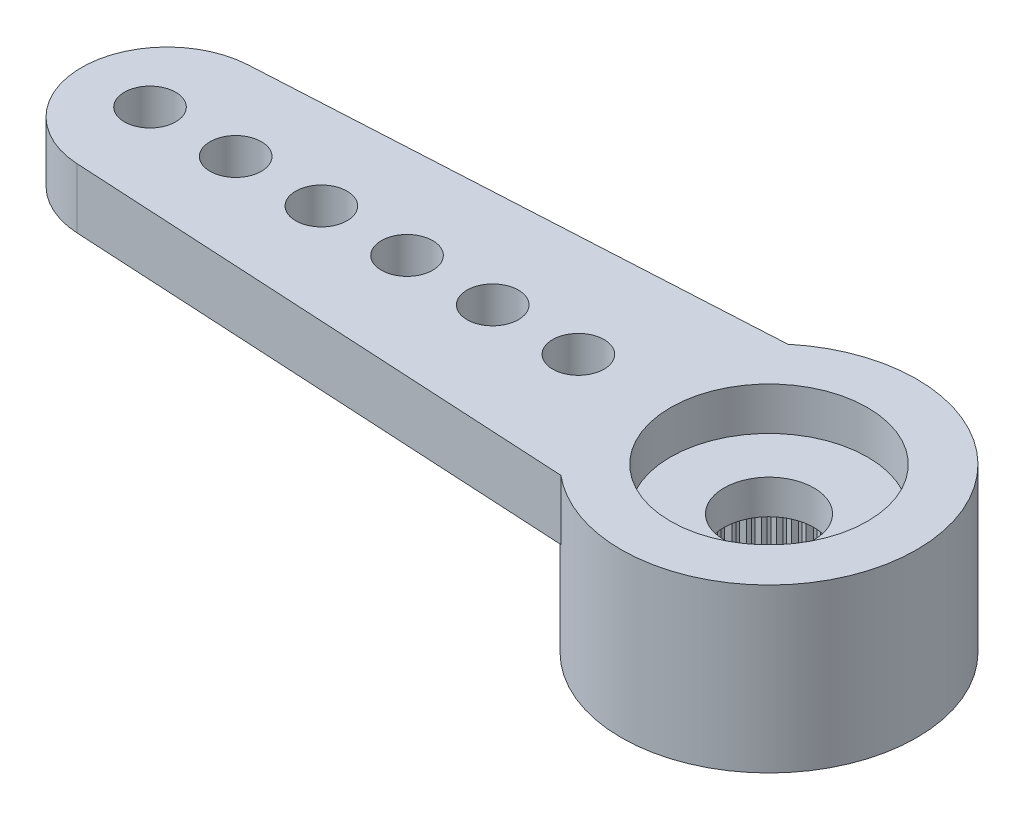
SolidWorks part; units mm, degrees
material "PVC Rígido"
ref_plane "Plano frontal" through (0, 0, 0) normal (0, 0, 1) x (1, 0, 0)
ref_plane "Plano superior" through (0, 0, 0) normal (0, 1, 0) x (1, 0, 0)
ref_plane "Plano direito" through (0, 0, 0) normal (1, 0, 0) x (0, 0, -1)
sketch "Esboço1" plane through (0, 0, 0) normal (0, 1, 0) x (1, 0, 0)
  line L0 (0, 0) -> (-14.05, 0) construction
  line L1 (-14.1591, 1.997) -> (-2.2091, 2.65)
  line L2 (-2.2091, -2.65) -> (-14.1591, -1.997)
  arc A0 (-2.2091, -2.65) -> (-2.2091, 2.65) centre (0, 0) ccw
  arc A1 (-14.1591, 1.997) -> (-14.1591, -1.997) centre (-14.05, 0) ccw
  dimension "D1" = 6.9
  dimension "D2" = 4
  dimension "D3" = 19.5
  dimension "D4" = 5.3
extrude "Ressalto-extrusão1" add sketch "Esboço1" against normal blind 1.4
sketch "Esboço2" plane through (0, -1.4, 0) normal (0, -1, 0) x (1, 0, 0)
  arc A0 (-2.2091, -2.65) -> (-2.2091, 2.65) centre (0, 0) ccw construction
  circle A1 centre (0, 0) radius 3.45
extrude "Ressalto-extrusão2" add sketch "Esboço2" along normal offset from surface (2.4 mm away) 3.8 up to face at (-7.242, 0, 0)
hole_wizard "Furo4" positions "Esboço9" profile "Esboço10" legacy end condition through all
sketch "Esboço9" plane through (0, 0, 0) normal (0, 1, 0) x (1, 0, 0)
  line L1 (-14.45, 0) -> (0, 0) construction
  arc A2 (-14.1591, 1.997) -> (-14.1591, -1.997) centre (-14.05, 0) ccw construction
  point P0 (-14.45, 0)
  point P19 (-16.05, 0)
  dimension "D1" = 1.6
sketch "Esboço10" plane through (-14.45, 0, 0) normal (1, 0, 0) x (0, 0, 1)
  line L0 (0, 0) -> (0, 3.8)
  line L1 (0, 3.8) -> (0.6, 3.8)
  line L2 (0.6, 3.8) -> (0.6, 0)
  line L3 (0.6, 0) -> (0, 0)
  line L4 (0, 110) -> (0, -10) construction
  dimension "Diameter" = 1.2
  dimension "Depth" = 3.8
pattern_linear "Padrão linear1" count 6 spacing 2 along (1, 0, 0) of "Furo4"
hole_wizard "Furo1" positions "Esboço3" profile "Esboço4" legacy
sketch "Esboço3" plane through (0, -3.8, 0) normal (0, -1, 0) x (-1, 0, 0)
  point P0 (0, 0)
sketch "Esboço4" plane through (0, -3.8, 0) normal (1, 0, 0) x (0, 0, -1)
  line L0 (0, 0) -> (0, 2)
  line L1 (0, 2) -> (2.475, 2)
  line L2 (2.475, 2) -> (2.475, 0)
  line L3 (2.475, 0) -> (0, 0)
  line L4 (0, 110) -> (0, -10) construction
  dimension "Diameter" = 4.95
  dimension "Depth" = 2
hole_wizard "Furo2" positions "Esboço5" profile "Esboço6" legacy
sketch "Esboço5" plane through (0, 0, 0) normal (0, 1, 0) x (1, 0, 0)
  point P0 (0, 0)
sketch "Esboço6" plane through (0, 0, 0) normal (1, 0, 0) x (0, 0, 1)
  line L0 (0, 0) -> (0, 1)
  line L1 (0, 1) -> (2.3, 1)
  line L2 (2.3, 1) -> (2.3, 0)
  line L3 (2.3, 0) -> (0, 0)
  line L4 (0, 110) -> (0, -10) construction
  dimension "Diameter" = 4.6
  dimension "Depth" = 1
hole_wizard "Furo3" positions "Esboço7" profile "Esboço8" legacy end condition through all
sketch "Esboço7" plane through (0, 0, 0) normal (0, 1, 0) x (1, 0, 0)
  point P0 (0, 0)
sketch "Esboço8" plane through (0, 0, 0) normal (1, 0, 0) x (0, 0, 1)
  line L0 (0, 0) -> (0, 3.8)
  line L1 (0, 3.8) -> (1.05, 3.8)
  line L2 (1.05, 3.8) -> (1.05, 0)
  line L3 (1.05, 0) -> (0, 0)
  line L4 (0, 110) -> (0, -10) construction
  dimension "Diameter" = 2.1
  dimension "Depth" = 3.8
sketch "Esboço11" plane through (0, -3.8, 0) normal (0, -1, 0) x (1, 0, 0)
  line L0 (-0.0981, 2.4731) -> (0, 2.375)
  line L1 (0, 2.375) -> (0.0981, 2.4731)
  line L2 (0, 0) -> (0, 2.475) construction
  circle A0 centre (0, 0) radius 2.375 construction
  circle A1 centre (0, 0) radius 2.475
  arc A2 (0.0981, 2.4731) -> (-0.0981, 2.4731) centre (0, 0) ccw
  dimension "D3" = 4.75
  dimension "D2" = 0.1
  dimension "D1" = 0
extrude "Ressalto-extrusão3" add sketch "Esboço11" against normal up to surface (2 mm away) up to face at (0, -1.8, 1.05)
pattern_circular "PadrãoCircular1" count 60 over 360 about axis through (0, 0, 0) along (0, 1, 0) of "Ressalto-extrusão3"
sketch "Sketch1" plane through (0, 0, 0) normal (0, 1, 0) x (1, 0, 0)
  line L2 (-2.2091, 2.65) -> (-14.1591, 1.997)
  line L3 (-14.1591, -1.997) -> (-2.2091, -2.65)
  line L4 (-2.2091, 2.65) -> (-14.1591, 1.997)
  line L5 (-14.1591, -1.997) -> (-2.2091, -2.65)
  circle A1 centre (-4.45, 0) radius 0.6
  arc A2 (-2.2091, -2.65) -> (-2.2091, 2.65) centre (0, 0) ccw
  arc A3 (-14.1591, 1.997) -> (-14.1591, -1.997) centre (-14.05, 0) ccw
  arc A4 (-2.2091, -2.65) -> (-2.2091, 2.65) centre (0, 0) ccw
  arc A5 (-14.1591, 1.997) -> (-14.1591, -1.997) centre (-14.05, 0) ccw
  circle A6 centre (-4.45, 0) radius 0.6
  circle A7 centre (0, 0) radius 2.3
  circle A8 centre (0, 0) radius 2.3
  circle A9 centre (-10.45, 0) radius 0.6
  circle A10 centre (-10.45, 0) radius 0.6
  circle A11 centre (-8.45, 0) radius 0.6
  circle A12 centre (-8.45, 0) radius 0.6
  circle A13 centre (-6.45, 0) radius 0.6
  circle A14 centre (-6.45, 0) radius 0.6
  circle A15 centre (-14.45, 0) radius 0.6
  circle A16 centre (-14.45, 0) radius 0.6
  circle A17 centre (-12.45, 0) radius 0.6
  circle A18 centre (-12.45, 0) radius 0.6
  dimension "D1" = 0
  dimension "D2" = 0
  dimension "D3" = 0
  dimension "D4" = 0
  dimension "D5" = 0
  dimension "D6" = 0
  dimension "D7" = 0
  dimension "D8" = 0
